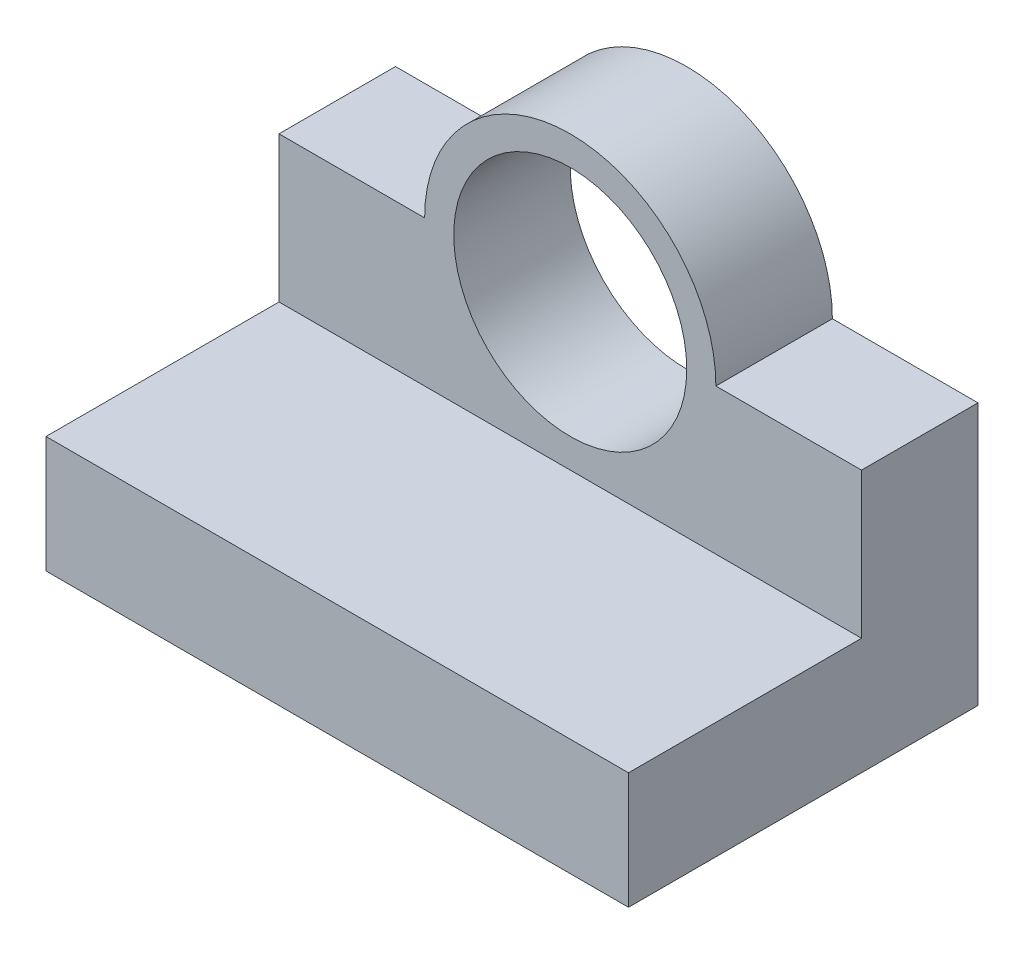
SolidWorks part; units mm, degrees
ref_plane "Front Plane" through (0, 0, 0) normal (0, 0, 1) x (1, 0, 0)
ref_plane "Top Plane" through (0, 0, 0) normal (0, 1, 0) x (1, 0, 0)
ref_plane "Right Plane" through (0, 0, 0) normal (1, 0, 0) x (0, 0, -1)
sketch "Sketch3" plane through (0, 0, 0) normal (0, 0, 1) x (1, 0, 0)
  line L0 (25, 12.5) -> (50, 12.5)
  line L1 (-50, -12.5) -> (50, -12.5)
  line L2 (-50, -12.5) -> (-50, 12.5)
  line L3 (-50, 12.5) -> (-25, 12.5)
  line L4 (50, -12.5) -> (50, 12.5)
  line L5 (-50, -12.5) -> (24.1503, 6.0376) construction
  line L6 (-50, 12.5) -> (50, -12.5) construction
  circle A1 centre (0, 12.5) radius 20
  arc A2 (25, 12.5) -> (-25, 12.5) centre (0, 12.5) ccw
  point P0 (0, 0)
  dimension "40" = 40
  dimension "D1" = 100
  dimension "D2" = 25
extrude "Boss-Extrude1" add sketch "Sketch3" along normal mid plane 20
sketch "Sketch5" plane through (0, 0, 10) normal (0, 0, 1) x (1, 0, 0)
  line L1 (-50, -12.5) -> (50, -12.5)
  line L2 (-50, -12.5) -> (-50, -32.5)
  line L3 (-50, -32.5) -> (50, -32.5)
  line L4 (50, -12.5) -> (50, -32.5)
  dimension "20" = 20
extrude "Boss-Extrude2" add sketch "Sketch5" along normal blind 60 from offset 20
